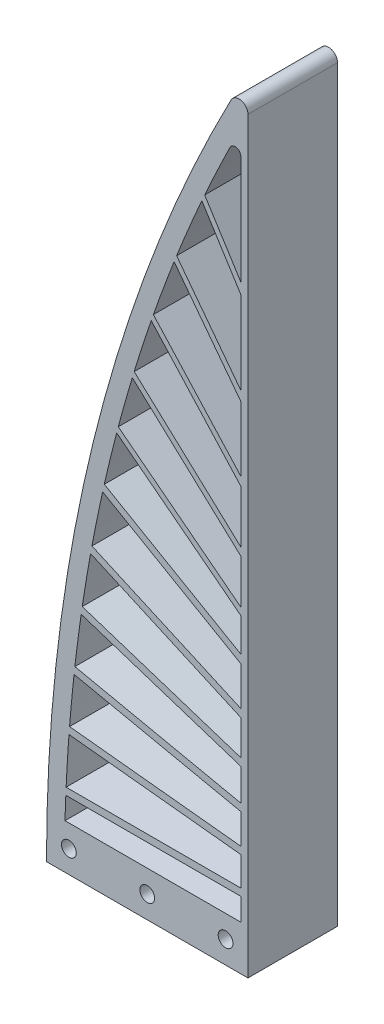
SolidWorks part; units mm, degrees
ref_plane "Front Plane" through (0, 0, 0) normal (0, 0, 1) x (1, 0, 0)
ref_plane "Top Plane" through (0, 0, 0) normal (0, 1, 0) x (1, 0, 0)
ref_plane "Right Plane" through (0, 0, 0) normal (1, 0, 0) x (0, 0, -1)
sketch "Sketch1" plane through (0, 0, 0) normal (0, 1, 0) x (1, 0, 0)
  line L1 (-9.5, 8) -> (9.5, 8) construction
  line L2 (-9.5, 8) -> (-9.5, -8) construction
  line L3 (-9.5, -8) -> (9.5, -8) construction
  line L4 (9.5, 8) -> (9.5, -8) construction
  line L5 (-9.5, 8) -> (9.5, -8) construction
  line L6 (-9.5, -8) -> (9.5, 8) construction
  line L7 (12, 10.5) -> (-12, 10.5)
  line L8 (12, 10.5) -> (12, -10.5)
  line L9 (12, -10.5) -> (-12, -10.5)
  line L10 (-12, 10.5) -> (-12, -10.5)
  line L11 (12, 10.5) -> (-12, -10.5) construction
  line L12 (12, -10.5) -> (-12, 10.5) construction
  circle A0 centre (-9.5, 8) radius 1.625
  circle A1 centre (9.5, 8) radius 1.625
  circle A2 centre (9.5, -8) radius 1.625
  circle A3 centre (-9.5, -8) radius 1.625
  point P0 (0, 0)
  point P10 (0, 0)
  dimension "D3" = 3.25
  dimension "D1" = 24
  dimension "D2" = 21
  dimension "D4" = 19
  dimension "D5" = 16
extrude "Boss-Extrude1" [suppressed] add sketch "Sketch1" along normal blind 7.5
sketch "Sketch5" plane through (0, 0, 0) normal (0, 0, 1) x (1, 0, 0)
  line L0 (0, 0) -> (0, 167.0412)
  line L1 (-45, 0) -> (0, 0)
  line L2 (-1.6, 10) -> (-40.8606, 10)
  line L98 (-1.6, 10) -> (-1.6, 158.1242)
  line L99 (-45, 0) -> (-45, 5) construction
  line L102 (-40.9777, 4) -> (-4, 4) construction
  line L103 (-4, 4) -> (-4, 158.6838) construction
  line L104 (0, 0) -> (0, 175) construction
  arc A1 (-3.7727, 167.9673) -> (-45, 0) centre (317.7778, 0) ccw
  arc A24 (-4, 158.6838) -> (-40.8606, 10) centre (317.7778, 0) ccw
  arc A25 (-4, 158.6838) -> (-40.9777, 4) centre (317.7778, 0) ccw construction
  arc A26 (-1.6, 158.1242) -> (-4, 158.6838) centre (-2.8652, 158.1242) ccw
  arc A27 (0, 175) -> (-45, 0) centre (317.7778, 0) ccw construction
  arc A28 (0, 167.0412) -> (-3.7727, 167.9673) centre (-2, 167.0412) ccw
  point P16 (0, 175)
  dimension "D7" = 2
  dimension "D2" = 175
  dimension "D5" = 10
  dimension "D6" = 1.6
  dimension "D1" = 5
  dimension "D3" = 45
  dimension "D4" = 4
extrude "Boss-Extrude4" add sketch "Sketch5" along normal blind 20
sketch "Sketch10" plane through (0, 0, 20) normal (0, 0, 1) x (1, 0, 0)
  line L0 (-40.6863, 15) -> (-1.6, 15)
  line L1 (-1.6, 10) -> (-1.6, 158.1242) construction
  line L2 (-1.6, 16.6) -> (-40.6158, 16.6)
  line L3 (-40.8606, 10) -> (-1.6, 10) construction
  line L4 (0, 10) -> (75, 10) construction
  line L5 (0, 0) -> (0, 167.0412) construction
  line L6 (-39.5299, 27.0651) -> (-0.6577, 22.9795)
  line L7 (-0.4905, 24.5707) -> (-39.2925, 28.649)
  line L8 (-37.1187, 38.9433) -> (1.1135, 30.8168)
  line L9 (1.4461, 32.3818) -> (-36.7171, 40.4936)
  line L10 (-33.4791, 50.5043) -> (3.6942, 38.426)
  line L11 (4.1886, 39.9477) -> (-32.9176, 52.0042)
  line L12 (-28.651, 61.6216) -> (7.0561, 45.7238)
  line L13 (7.7069, 47.1854) -> (-27.9358, 63.0546)
  line L14 (-22.6873, 72.1733) -> (11.1625, 52.6301)
  line L15 (11.9625, 54.0158) -> (-21.8262, 73.5237)
  line L20 (0, 68.0707) -> (75, 10) construction
  line L21 (-1.6, 69.3095) -> (-29.326, 90.7771)
  line L22 (-1.6, 70.9537) -> (-28.966, 92.1425)
  line L23 (3.8607, 75.76) -> (-21.8888, 99.5623)
  line L24 (4.0039, 77.3979) -> (-21.4112, 100.8912)
  line L25 (9.8627, 81.7099) -> (-13.7142, 107.6659)
  line L26 (10.1482, 83.3291) -> (-13.1226, 108.9481)
  line L27 (16.3605, 87.1142) -> (-4.8645, 115.0262)
  line L28 (16.7861, 88.7023) -> (-4.1634, 116.252)
  line L29 (23.3046, 91.9315) -> (4.593, 121.5872)
  line L30 (23.8669, 93.4765) -> (5.3983, 122.7472)
  arc A0 (-4, 158.6838) -> (-40.8606, 10) centre (317.7778, 0) ccw construction
  arc A1 (-4, 158.6838) -> (-40.8606, 10) centre (317.7778, 0) ccw
  point P54 (75, 10)
  point P67 (75, 10)
  dimension "D1" = 1.6
  dimension "D2" = 5
  dimension "D3" = 75
  dimension "D5" = 6
  dimension "D6" = 1.3
  dimension "D9" = 5
  dimension "D7" = 7.75
  dimension "D4" = 6
  dimension "D8" = 5
sketch "Sketch11" plane through (0, 0, 20) normal (0, 0, 1) x (1, 0, 0)
  line L0 (-40.6863, 15) -> (-1.6, 15)
  line L1 (-1.6, 10) -> (-1.6, 158.1242) construction
  line L2 (-1.6, 15) -> (-1.6, 16.6)
  line L3 (-40.6158, 16.6) -> (-1.6, 16.6)
  line L4 (-39.9742, 27.1118) -> (-1.6, 23.0785)
  line L5 (-39.5299, 27.0651) -> (-0.6577, 22.9795) construction
  line L6 (-39.8496, 28.7075) -> (-1.6, 24.6873)
  line L7 (-0.4905, 24.5707) -> (-39.2925, 28.649) construction
  line L8 (-38.8401, 39.3092) -> (-1.6, 31.3935)
  line L9 (-38.6603, 40.9067) -> (-1.6, 33.0293)
  line L10 (1.4461, 32.3818) -> (-36.7171, 40.4936) construction
  line L11 (-37.1187, 38.9433) -> (1.1135, 30.8168) construction
  line L12 (-37.2511, 51.7299) -> (-1.6, 40.1462)
  line L13 (-33.4791, 50.5043) -> (3.6942, 38.426) construction
  line L14 (-37.0135, 53.3351) -> (-1.6, 41.8285)
  line L15 (4.1886, 39.9477) -> (-32.9176, 52.0042) construction
  line L16 (-35.1517, 64.5159) -> (-1.6, 49.5777)
  line L17 (-28.651, 61.6216) -> (7.0561, 45.7238) construction
  line L18 (-34.8521, 66.1339) -> (-1.6, 51.3291)
  line L19 (7.7069, 47.1854) -> (-27.9358, 63.0546) construction
  line L29 (-29.326, 90.7771) -> (-1.6, 69.3095)
  line L31 (-28.966, 92.1425) -> (-1.6, 70.9537)
  line L33 (-1.6, 61.8461) -> (-32.0923, 79.4508)
  line L35 (-32.4597, 77.8154) -> (-1.6, 59.9985)
  line L36 (-25.8343, 103.2095) -> (-1.6, 80.8077)
  line L37 (3.8607, 75.76) -> (-21.8888, 99.5623) construction
  line L38 (-25.4158, 104.5929) -> (-1.6, 82.578)
  line L39 (4.0039, 77.3979) -> (-21.4112, 100.8912) construction
  line L40 (-21.608, 116.3562) -> (-1.6, 94.3293)
  line L41 (9.8627, 81.7099) -> (-13.7142, 107.6659) construction
  line L42 (-21.1244, 117.7573) -> (-1.6, 96.2628)
  line L43 (10.1482, 83.3291) -> (-13.1226, 108.9481) construction
  line L44 (-16.4946, 130.3205) -> (-1.6, 110.7332)
  line L45 (16.3605, 87.1142) -> (-4.8645, 115.0262) construction
  line L46 (-15.9388, 131.7373) -> (-1.6, 112.8809)
  line L47 (16.7861, 88.7023) -> (-4.1634, 116.252) construction
  line L48 (-1.6, 23.0785) -> (-1.6, 24.6873)
  line L49 (-1.6, 31.3935) -> (-1.6, 33.0293)
  line L50 (-1.6, 40.1462) -> (-1.6, 41.8285)
  line L51 (-1.6, 49.5777) -> (-1.6, 51.3291)
  line L53 (-1.6, 110.7332) -> (-1.6, 112.8809)
  line L54 (-1.6, 94.3293) -> (-1.6, 96.2628)
  line L55 (-1.6, 80.8077) -> (-1.6, 82.578)
  line L59 (-22.6873, 72.1733) -> (11.1625, 52.6301) construction
  line L60 (11.9625, 54.0158) -> (-21.8262, 73.5237) construction
  line L61 (-1.6, 59.9985) -> (-1.6, 61.8461)
  line L62 (-10.3054, 145.1996) -> (-1.6, 131.4025)
  line L63 (-9.6695, 146.628) -> (-1.6, 133.8387)
  line L64 (23.8669, 93.4765) -> (5.3983, 122.7472) construction
  line L65 (23.3046, 91.9315) -> (4.593, 121.5872) construction
  line L66 (-1.6, 133.8387) -> (-1.6, 131.4025)
  arc A0 (-4, 158.6838) -> (-40.8606, 10) centre (317.7778, 0) ccw construction
  arc A2 (-40.6158, 16.6) -> (-40.6863, 15) centre (317.7778, 0) ccw
  arc A8 (-25.4158, 104.5929) -> (-25.8343, 103.2095) centre (317.7778, 0) ccw
  arc A13 (-9.6695, 146.628) -> (-10.3054, 145.1996) centre (317.7778, 0) ccw
  arc A14 (-40.6158, 16.6) -> (-40.6863, 15) centre (317.7778, 0) ccw
  arc A15 (-39.8496, 28.7075) -> (-39.9742, 27.1118) centre (317.7778, 0) ccw
  arc A16 (-38.6603, 40.9067) -> (-38.8401, 39.3092) centre (317.7778, 0) ccw
  arc A17 (-37.0135, 53.3351) -> (-37.2511, 51.7299) centre (317.7778, 0) ccw
  arc A18 (-34.8521, 66.1339) -> (-35.1517, 64.5159) centre (317.7778, 0) ccw
  arc A19 (-32.0923, 79.4508) -> (-32.4597, 77.8154) centre (317.7778, 0) ccw
  arc A20 (-28.966, 92.1425) -> (-29.326, 90.7771) centre (317.7778, 0) ccw
  arc A21 (-25.4158, 104.5929) -> (-25.8343, 103.2095) centre (317.7778, 0) ccw
  arc A22 (-21.1244, 117.7573) -> (-21.608, 116.3562) centre (317.7778, 0) ccw
  arc A23 (-15.9388, 131.7373) -> (-16.4946, 130.3205) centre (317.7778, 0) ccw
  arc M26 (-40.8606, 10) -> (-4, 158.6838) centre (317.7778, 0) cw
  line M28 (-1.6, 158.1242) -> (-1.6, 10)
extrude "Boss-Extrude7" add sketch "Sketch11" against normal up to surface (20 mm away) contours L3 L0 M26 M28 | L6 L4 M26 M28 | L9 L8 M26 M28 | L14 L12 M26 M28 | L18 L16 M26 M28 | L35 L33 M26 M28 | L31 L29 M26 M28 | L38 L36 M26 M28 | L42 L40 M26 M28 | L46 L44 M26 M28 | L63 L62 M26 M28 up to face at (-14.6414, 84.7452, 0)
sketch "Sketch12" plane through (0, 0, 20) normal (0, 0, 1) x (1, 0, 0)
  line L0 (-40, 5) -> (-22.5, 5) construction
  line L1 (-40.8606, 10) -> (-1.6, 10) construction
  line L2 (-22.5, 0) -> (-22.5, 10) construction
  line L3 (-45, 0) -> (0, 0) construction
  line L4 (-22.5, 5) -> (-5, 5) construction
  line L6 (-5, 5) -> (0, 5) construction
  line L7 (0, 0) -> (0, 167.0412) construction
  circle A1 centre (-40, 5) radius 1.65
  circle A2 centre (-22.5, 5) radius 1.65
  circle A3 centre (-5, 5) radius 1.65
  dimension "D1" = 3.3
  dimension "D2" = 17.5
extrude "Cut-Extrude1" cut sketch "Sketch12" against normal through all
equation "\"Middle Finger Width\"= 30mm"
equation "\"Finger Length\"= 45"
equation "\"Finger Height\"= \"Finger Length\" * 3.5"
equation "\"D3@Sketch5\"=\"Finger Length\""
equation "\"Base Height\"= 10mm"
equation "\"D1@Sketch5\"= \"Base Height\" / 2"
equation "\"D5@Sketch5\"= \"Base Height\""
equation "\"Thick Walls\"= 1.6mm"
equation "\"Thin Walls\"= 1.3mm"
equation "\"D6@Sketch5\"=\"Thick Walls\""
equation "\"D2@Sketch10\"=\"Base Height\"/2"
equation "\"D1@Sketch10\"=\"Thick Walls\" "
equation "\"D6@Sketch10\"=\"Thin Walls\""
equation "\"D1@Boss-Extrude4\"  = 2 * \"Middle Finger Width\" /3"
equation "\"Outer Finger Width\"= 2 * \"Middle Finger Width\" / 3"
